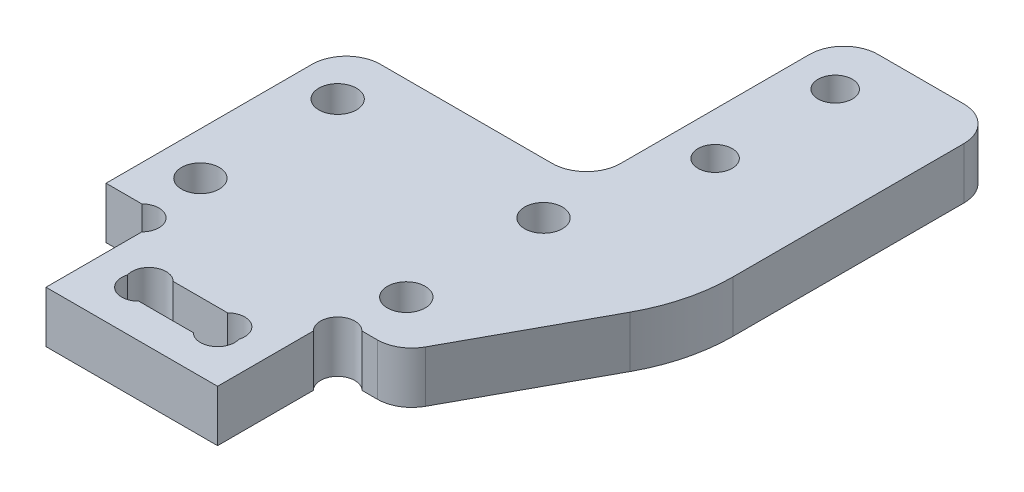
SolidWorks part; units mm, degrees
material "Thornel Mat VMA"
ref_plane "前视基准面" through (0, 0, 0) normal (0, 0, 1) x (1, 0, 0)
ref_plane "上视基准面" through (0, 0, 0) normal (0, 1, 0) x (1, 0, 0)
ref_plane "右视基准面" through (0, 0, 0) normal (1, 0, 0) x (0, 0, -1)
sketch "草图1" plane through (0, 0, 0) normal (0, 1, 0) x (1, 0, 0)
  line L1 (-8.5, -7) -> (8.5, -7)
  line L2 (-8.5, -7) -> (-8.5, 7)
  line L3 (-8.5, 7) -> (8.5, 7)
  line L4 (8.5, -7) -> (8.5, 7)
  line L5 (0, 7) -> (0, -7) construction
  line L6 (-8.5, 0) -> (8.5, 0) construction
  circle A0 centre (-6, 4) radius 1.1
  circle A1 centre (6, 4) radius 1.1
  circle A2 centre (6, -4) radius 1.1
  circle A3 centre (-6, -4) radius 1.1
  point P0 (0, 0)
  dimension "D1" = 2.2
  dimension "D2" = 12
  dimension "D3" = 8
  dimension "D4" = 17
  dimension "D5" = 14
extrude "凸台-拉伸1" add sketch "草图1" along normal blind 3
sketch "草图2" plane through (0, 3, 0) normal (0, 1, 0) x (1, 0, 0)
  line L0 (5.5, 7) -> (8.5, 7)
  line L15 (5.5, 7) -> (5.5, 22)
  line L16 (5.5, 22) -> (14.5, 22)
  line L17 (14.5, 4) -> (14.5, 22)
  line L18 (14.5, 4) -> (8.5, -7)
  line L19 (8.5, 7) -> (-8.5, 7) construction
  line L20 (8.5, 7) -> (8.5, -7)
  dimension "D1" = 3
  dimension "D2" = 9
  dimension "D3" = 3
  dimension "D4" = 15
extrude "凸台-拉伸3" add sketch "草图2" against normal up to surface (3 mm away) up to face at (6, 0, 5.1)
sketch "草图3" plane through (0, 3, 0) normal (0, 1, 0) x (1, 0, 0)
  line L0 (8, 19) -> (8, -1.6698) construction
  line L1 (5.5, 7) -> (5.5, 22) construction
  line L2 (5.5, 22) -> (14.5, 22) construction
  circle A0 centre (8, 19) radius 1
  circle A1 centre (8, 19) radius 3 construction
  circle A2 centre (8, 12) radius 1
  circle A3 centre (8, 12) radius 3 construction
  dimension "D1" = 2
  dimension "D2" = 6
  dimension "D5" = 7
  dimension "D3" = 2.5
  dimension "D4" = 3
extrude "切除-拉伸1" cut sketch "草图3" against normal through all
sketch "草图4" plane through (0, 3, 0) normal (0, 1, 0) x (1, 0, 0)
  line L0 (0, -7) -> (0, -14) construction
  line L5 (-8.5, -7) -> (8.5, -7) construction
  line L6 (-5, -7) -> (5, -7)
  line L7 (-5, -7) -> (-5, -14)
  line L8 (-5, -14) -> (5, -14)
  line L9 (5, -7) -> (5, -14)
  line L19 (-3, -12) -> (3, -12)
  line L20 (-3, -12) -> (-3, -10)
  line L21 (-3, -10) -> (3, -10)
  line L22 (3, -12) -> (3, -10)
  line L23 (-3, -12) -> (3, -10) construction
  line L24 (-3, -10) -> (3, -12) construction
  point P4 (0, -11)
  dimension "D1" = 2
  dimension "D2" = 10
  dimension "D3" = 3
  dimension "D4" = 2
  dimension "D5" = 6
extrude "凸台-拉伸4" add sketch "草图4" against normal up to surface (3 mm away)
sketch "草图7" plane through (0, 3, 0) normal (0, 1, 0) x (1, 0, 0)
  line L1 (0, -14) -> (0, -12) construction
  line L2 (-5, -14) -> (5, -14) construction
  line L3 (-3, -12) -> (3, -12) construction
  line L4 (5.7071, -7.7071) -> (5, -7) construction
  line L5 (5, -7) -> (8.5, -7) construction
  circle A2 centre (5.7071, -7.7071) radius 1
  circle A3 centre (-5.7071, -7.7071) radius 1
  dimension "D1" = 2
  dimension "D2" = 45
extrude "切除-拉伸4" cut sketch "草图7" against normal through all
fillet "圆角1" radius 10 1 edges at (14.5, 1.5, -4)
fillet "圆角2" radius 2 5 edges at (14.5, 1.5, -22) (5.5, 1.5, -7) (-8.5, 1.5, -7) (8.5, 1.5, 7) (5.5, 1.5, -22)
sketch "草图8" plane through (0, 3, 0) normal (0, 1, 0) x (1, 0, 0)
  line L0 (3, -11) -> (0, -11) construction
  line L1 (3, -12) -> (3, -10) construction
  line L2 (0, -11) -> (0, -12) construction
  line L3 (-3, -12) -> (3, -12) construction
  line L4 (-2.2929, -10.7071) -> (-3, -10) construction
  line L5 (-1.5858, -10) -> (-3, -10) construction
  line L6 (-3, -10) -> (3, -10) construction
  line L7 (-3, -10) -> (-3, -11.4142) construction
  line L8 (-3, -12) -> (-3, -10) construction
  arc A4 (-1.3367, -11) -> (-3.249, -11) centre (-2.2929, -10.7071) ccw
  arc A5 (-1.3367, -11) -> (-3.249, -11) centre (-2.2929, -11.2929) cw
  arc A6 (1.3367, -11) -> (3.249, -11) centre (2.2929, -11.2929) ccw
  arc A7 (1.3367, -11) -> (3.249, -11) centre (2.2929, -10.7071) cw
  dimension "D1" = 2
  dimension "D2" = 45
extrude "切除-拉伸5" cut sketch "草图8" against normal through all
